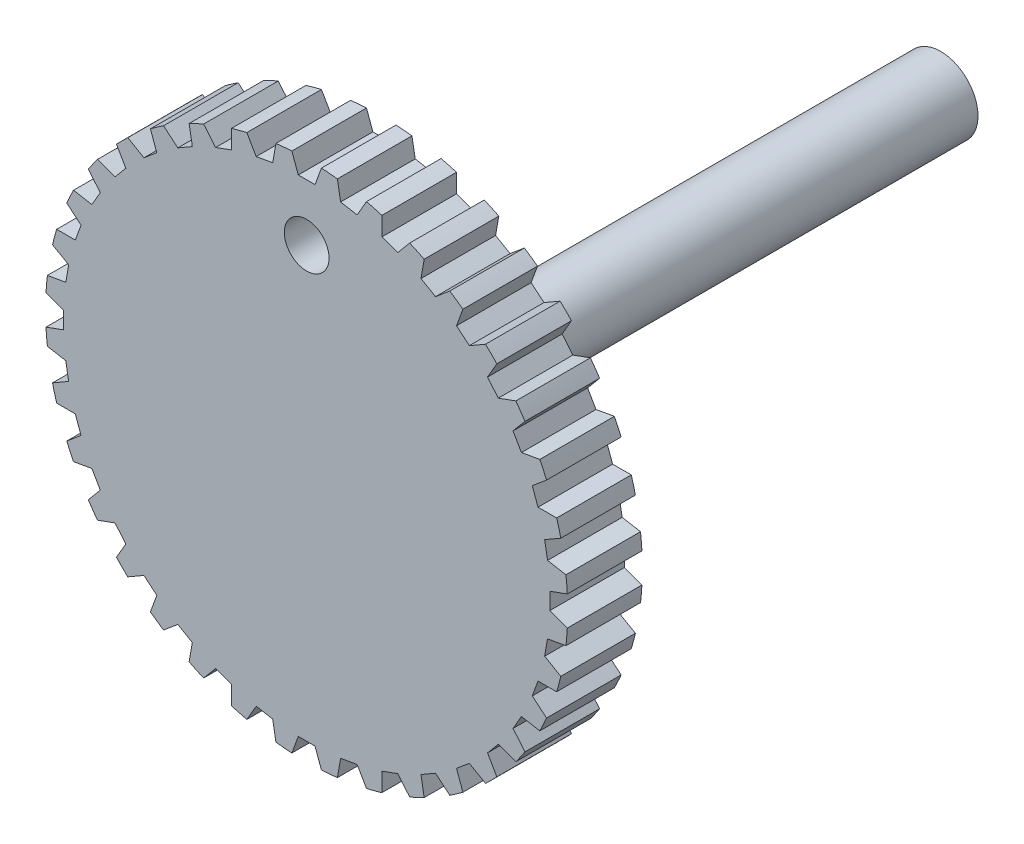
SolidWorks part; units mm, degrees
ref_plane "Front Plane" through (0, 0, 0) normal (0, 0, 1) x (1, 0, 0)
ref_plane "Top Plane" through (0, 0, 0) normal (0, 1, 0) x (1, 0, 0)
ref_plane "Right Plane" through (0, 0, 0) normal (1, 0, 0) x (0, 0, -1)
sketch "Sketch1" plane through (0, 0, 0) normal (0, 0, 1) x (1, 0, 0)
  line L0 (-3.9601, 69.8879) -> (-2.25, 65.1894)
  line L1 (-2.25, 65.1894) -> (2.25, 65.1894)
  line L2 (2.25, 65.1894) -> (3.9601, 69.8879)
  line L3 (13.5358, 63.8083) -> (16.0358, 68.1385)
  line L4 (8.236, 69.5138) -> (9.1042, 64.5898)
  line L5 (9.1042, 64.5898) -> (13.5358, 63.8083)
  line L6 (24.4104, 60.4885) -> (27.6243, 64.3187)
  line L7 (20.1818, 67.0276) -> (20.1818, 62.0276)
  line L8 (20.1818, 62.0276) -> (24.4104, 60.4885)
  line L9 (34.5433, 55.3307) -> (38.3735, 58.5446)
  line L10 (31.5144, 62.5047) -> (30.6462, 57.5807)
  line L11 (30.6462, 57.5807) -> (34.5433, 55.3307)
  line L12 (43.6266, 48.4917) -> (47.9567, 50.9917)
  line L13 (41.8895, 56.0827) -> (40.1794, 51.3843)
  line L14 (40.1794, 51.3843) -> (43.6266, 48.4917)
  line L15 (51.3843, 40.1794) -> (56.0827, 41.8895)
  line L16 (50.9917, 47.9567) -> (48.4917, 43.6266)
  line L17 (48.4917, 43.6266) -> (51.3843, 40.1794)
  line L18 (57.5807, 30.6462) -> (62.5047, 31.5144)
  line L19 (58.5446, 38.3735) -> (55.3307, 34.5433)
  line L20 (55.3307, 34.5433) -> (57.5807, 30.6462)
  line L21 (62.0276, 20.1818) -> (67.0276, 20.1818)
  line L22 (64.3187, 27.6243) -> (60.4885, 24.4104)
  line L23 (60.4885, 24.4104) -> (62.0276, 20.1818)
  line L24 (64.5898, 9.1042) -> (69.5138, 8.236)
  line L25 (68.1385, 16.0358) -> (63.8083, 13.5358)
  line L26 (63.8083, 13.5358) -> (64.5898, 9.1042)
  line L27 (65.1894, -2.25) -> (69.8879, -3.9601)
  line L28 (69.8879, 3.9601) -> (65.1894, 2.25)
  line L29 (65.1894, 2.25) -> (65.1894, -2.25)
  line L30 (63.8083, -13.5358) -> (68.1385, -16.0358)
  line L31 (69.5138, -8.236) -> (64.5898, -9.1042)
  line L32 (64.5898, -9.1042) -> (63.8083, -13.5358)
  line L33 (60.4885, -24.4104) -> (64.3187, -27.6243)
  line L34 (67.0276, -20.1818) -> (62.0276, -20.1818)
  line L35 (62.0276, -20.1818) -> (60.4885, -24.4104)
  line L36 (55.3307, -34.5433) -> (58.5446, -38.3735)
  line L37 (62.5047, -31.5144) -> (57.5807, -30.6462)
  line L38 (57.5807, -30.6462) -> (55.3307, -34.5433)
  line L39 (48.4917, -43.6266) -> (50.9917, -47.9567)
  line L40 (56.0827, -41.8895) -> (51.3843, -40.1794)
  line L41 (51.3843, -40.1794) -> (48.4917, -43.6266)
  line L42 (40.1794, -51.3843) -> (41.8895, -56.0827)
  line L43 (47.9567, -50.9917) -> (43.6266, -48.4917)
  line L44 (43.6266, -48.4917) -> (40.1794, -51.3843)
  line L45 (30.6462, -57.5807) -> (31.5144, -62.5047)
  line L46 (38.3735, -58.5446) -> (34.5433, -55.3307)
  line L47 (34.5433, -55.3307) -> (30.6462, -57.5807)
  line L48 (20.1818, -62.0276) -> (20.1818, -67.0276)
  line L49 (27.6243, -64.3187) -> (24.4104, -60.4885)
  line L50 (24.4104, -60.4885) -> (20.1818, -62.0276)
  line L51 (9.1042, -64.5898) -> (8.236, -69.5138)
  line L52 (16.0358, -68.1385) -> (13.5358, -63.8083)
  line L53 (13.5358, -63.8083) -> (9.1042, -64.5898)
  line L54 (-2.25, -65.1894) -> (-3.9601, -69.8879)
  line L55 (3.9601, -69.8879) -> (2.25, -65.1894)
  line L56 (2.25, -65.1894) -> (-2.25, -65.1894)
  line L57 (-13.5358, -63.8083) -> (-16.0358, -68.1385)
  line L58 (-8.236, -69.5138) -> (-9.1042, -64.5898)
  line L59 (-9.1042, -64.5898) -> (-13.5358, -63.8083)
  line L60 (-24.4104, -60.4885) -> (-27.6243, -64.3187)
  line L61 (-20.1818, -67.0276) -> (-20.1818, -62.0276)
  line L62 (-20.1818, -62.0276) -> (-24.4104, -60.4885)
  line L63 (-34.5433, -55.3307) -> (-38.3735, -58.5446)
  line L64 (-31.5144, -62.5047) -> (-30.6462, -57.5807)
  line L65 (-30.6462, -57.5807) -> (-34.5433, -55.3307)
  line L66 (-43.6266, -48.4917) -> (-47.9567, -50.9917)
  line L67 (-41.8895, -56.0827) -> (-40.1794, -51.3843)
  line L68 (-40.1794, -51.3843) -> (-43.6266, -48.4917)
  line L69 (-51.3843, -40.1794) -> (-56.0827, -41.8895)
  line L70 (-50.9917, -47.9567) -> (-48.4917, -43.6266)
  line L71 (-48.4917, -43.6266) -> (-51.3843, -40.1794)
  line L72 (-57.5807, -30.6462) -> (-62.5047, -31.5144)
  line L73 (-58.5446, -38.3735) -> (-55.3307, -34.5433)
  line L74 (-55.3307, -34.5433) -> (-57.5807, -30.6462)
  line L75 (-62.0276, -20.1818) -> (-67.0276, -20.1818)
  line L76 (-64.3187, -27.6243) -> (-60.4885, -24.4104)
  line L77 (-60.4885, -24.4104) -> (-62.0276, -20.1818)
  line L78 (-64.5898, -9.1042) -> (-69.5138, -8.236)
  line L79 (-68.1385, -16.0358) -> (-63.8083, -13.5358)
  line L80 (-63.8083, -13.5358) -> (-64.5898, -9.1042)
  line L81 (-65.1894, 2.25) -> (-69.8879, 3.9601)
  line L82 (-69.8879, -3.9601) -> (-65.1894, -2.25)
  line L83 (-65.1894, -2.25) -> (-65.1894, 2.25)
  line L84 (-63.8083, 13.5358) -> (-68.1385, 16.0358)
  line L85 (-69.5138, 8.236) -> (-64.5898, 9.1042)
  line L86 (-64.5898, 9.1042) -> (-63.8083, 13.5358)
  line L87 (-60.4885, 24.4104) -> (-64.3187, 27.6243)
  line L88 (-67.0276, 20.1818) -> (-62.0276, 20.1818)
  line L89 (-62.0276, 20.1818) -> (-60.4885, 24.4104)
  line L90 (-55.3307, 34.5433) -> (-58.5446, 38.3735)
  line L91 (-62.5047, 31.5144) -> (-57.5807, 30.6462)
  line L92 (-57.5807, 30.6462) -> (-55.3307, 34.5433)
  line L93 (-48.4917, 43.6266) -> (-50.9917, 47.9567)
  line L94 (-56.0827, 41.8895) -> (-51.3843, 40.1794)
  line L95 (-51.3843, 40.1794) -> (-48.4917, 43.6266)
  line L96 (-40.1794, 51.3843) -> (-41.8895, 56.0827)
  line L97 (-47.9567, 50.9917) -> (-43.6266, 48.4917)
  line L98 (-43.6266, 48.4917) -> (-40.1794, 51.3843)
  line L99 (-30.6462, 57.5807) -> (-31.5144, 62.5047)
  line L100 (-38.3735, 58.5446) -> (-34.5433, 55.3307)
  line L101 (-34.5433, 55.3307) -> (-30.6462, 57.5807)
  line L102 (-20.1818, 62.0276) -> (-20.1818, 67.0276)
  line L103 (-27.6243, 64.3187) -> (-24.4104, 60.4885)
  line L104 (-24.4104, 60.4885) -> (-20.1818, 62.0276)
  line L105 (-9.1042, 64.5898) -> (-8.236, 69.5138)
  line L106 (-16.0358, 68.1385) -> (-13.5358, 63.8083)
  line L107 (-13.5358, 63.8083) -> (-9.1042, 64.5898)
  arc A0 (-62.5047, 31.5144) -> (-64.3187, 27.6243) centre (0, 0) ccw
  arc A2 (-56.0827, 41.8895) -> (-58.5446, 38.3735) centre (0, 0) ccw
  arc A3 (-47.9567, 50.9917) -> (-50.9917, 47.9567) centre (0, 0) ccw
  arc A4 (-38.3735, 58.5446) -> (-41.8895, 56.0827) centre (0, 0) ccw
  arc A5 (-27.6243, 64.3187) -> (-31.5144, 62.5047) centre (0, 0) ccw
  arc A6 (-16.0358, 68.1385) -> (-20.1818, 67.0276) centre (0, 0) ccw
  arc A7 (-3.9601, 69.8879) -> (-8.236, 69.5138) centre (0, 0) ccw
  arc A8 (8.236, 69.5138) -> (3.9601, 69.8879) centre (0, 0) ccw
  arc A9 (20.1818, 67.0276) -> (16.0358, 68.1385) centre (0, 0) ccw
  arc A10 (31.5144, 62.5047) -> (27.6243, 64.3187) centre (0, 0) ccw
  arc A11 (41.8895, 56.0827) -> (38.3735, 58.5446) centre (0, 0) ccw
  arc A12 (58.5446, 38.3735) -> (56.0827, 41.8895) centre (0, 0) ccw
  arc A13 (50.9917, 47.9567) -> (47.9567, 50.9917) centre (0, 0) ccw
  arc A14 (64.3187, 27.6243) -> (62.5047, 31.5144) centre (0, 0) ccw
  arc A15 (68.1385, 16.0358) -> (67.0276, 20.1818) centre (0, 0) ccw
  arc A16 (69.8879, 3.9601) -> (69.5138, 8.236) centre (0, 0) ccw
  arc A17 (67.0276, -20.1818) -> (68.1385, -16.0358) centre (0, 0) ccw
  arc A18 (69.5138, -8.236) -> (69.8879, -3.9601) centre (0, 0) ccw
  arc A19 (62.5047, -31.5144) -> (64.3187, -27.6243) centre (0, 0) ccw
  arc A20 (56.0827, -41.8895) -> (58.5446, -38.3735) centre (0, 0) ccw
  arc A21 (47.9567, -50.9917) -> (50.9917, -47.9567) centre (0, 0) ccw
  arc A22 (38.3735, -58.5446) -> (41.8895, -56.0827) centre (0, 0) ccw
  arc A23 (27.6243, -64.3187) -> (31.5144, -62.5047) centre (0, 0) ccw
  arc A24 (16.0358, -68.1385) -> (20.1818, -67.0276) centre (0, 0) ccw
  arc A25 (3.9601, -69.8879) -> (8.236, -69.5138) centre (0, 0) ccw
  arc A26 (-8.236, -69.5138) -> (-3.9601, -69.8879) centre (0, 0) ccw
  arc A27 (-20.1818, -67.0276) -> (-16.0358, -68.1385) centre (0, 0) ccw
  arc A28 (-31.5144, -62.5047) -> (-27.6243, -64.3187) centre (0, 0) ccw
  arc A29 (-41.8895, -56.0827) -> (-38.3735, -58.5446) centre (0, 0) ccw
  arc A30 (-50.9917, -47.9567) -> (-47.9567, -50.9917) centre (0, 0) ccw
  arc A31 (-58.5446, -38.3735) -> (-56.0827, -41.8895) centre (0, 0) ccw
  arc A32 (-64.3187, -27.6243) -> (-62.5047, -31.5144) centre (0, 0) ccw
  arc A33 (-68.1385, -16.0358) -> (-67.0276, -20.1818) centre (0, 0) ccw
  arc A34 (-69.8879, -3.9601) -> (-69.5138, -8.236) centre (0, 0) ccw
  arc A35 (-69.5138, 8.236) -> (-69.8879, 3.9601) centre (0, 0) ccw
  arc A36 (-67.0276, 20.1818) -> (-68.1385, 16.0358) centre (0, 0) ccw
  point P6 (0, 65.1894)
  point P152 (0, 0)
  dimension "D1" = 140
  dimension "D3" = 70
  dimension "D4" = 70
  dimension "D5" = 5
  dimension "D6" = 4.5
  dimension "D7" = 36
extrude "Boss-Extrude1" add sketch "Sketch1" along normal blind 20
sketch "Sketch2" plane through (0, 0, 0) normal (0, 0, 1) x (1, 0, 0)
  circle A0 centre (0, 0) radius 10
  dimension "D1" = 20
extrude "Boss-Extrude2" add sketch "Sketch2" against normal blind 150
sketch "Sketch3" plane through (0, 0, 20) normal (0, 0, 1) x (1, 0, 0)
  circle A0 centre (0, 50) radius 6
  dimension "D1" = 12
  dimension "D2" = 50
extrude "Cut-Extrude1" cut sketch "Sketch3" against normal through all
